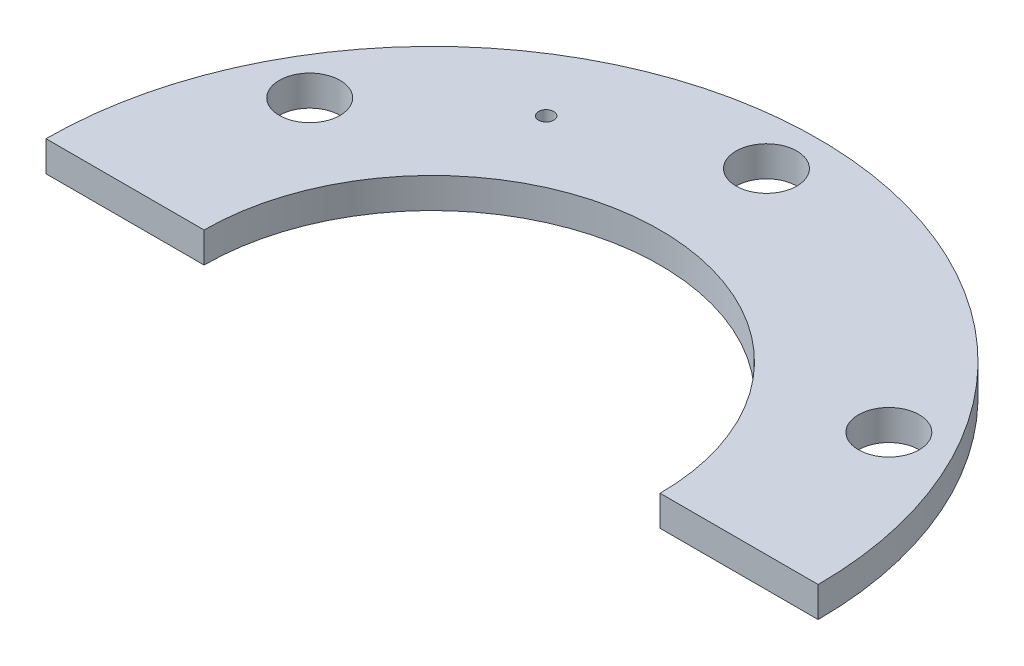
SolidWorks part; units mm, degrees
material "ABS"
ref_plane "Front Plane" through (0, 0, 0) normal (0, 0, 1) x (1, 0, 0)
ref_plane "Top Plane" through (0, 0, 0) normal (0, 1, 0) x (1, 0, 0)
ref_plane "Right Plane" through (0, 0, 0) normal (1, 0, 0) x (0, 0, -1)
sketch "Sketch1" plane through (0, 0, 0) normal (0, 1, 0) x (1, 0, 0)
  circle A0 centre (0, 0) radius 12.7
  dimension "D1" = 25.4
extrude "Boss-Extrude1" add sketch "Sketch1" along normal blind 1
sketch "Sketch19" plane through (0, 1, 0) normal (0, 1, 0) x (1, 0, 0)
  circle A0 centre (0, 11) radius 1
  circle A1 centre (9.5263, 5.5) radius 1
  circle A2 centre (9.5263, -5.5) radius 1
  circle A3 centre (0, -11) radius 1
  circle A4 centre (-9.5263, -5.5) radius 1
  circle A5 centre (-9.5263, 5.5) radius 1
  point P13 (0, 0)
  dimension "D1" = 2
  dimension "D2" = 11
  dimension "D3" = 6
extrude "Cut-Extrude1" cut sketch "Sketch19" against normal through all both and the other way through all
sketch "Sketch20" plane through (0, 1, 0) normal (0, 1, 0) x (1, 0, 0)
  circle A0 centre (0, 0) radius 7.5
  dimension "D1" = 15
extrude "Cut-Extrude2" cut sketch "Sketch20" against normal through all both and the other way through all
sketch "Sketch21" plane through (0, 0, 0) normal (0, 0, 1) x (1, 0, 0)
  line L1 (-36.7533, 32.3113) -> (29.1209, 32.3113)
  line L2 (-36.7533, 32.3113) -> (-36.7533, -19.668)
  line L3 (-36.7533, -19.668) -> (29.1209, -19.668)
  line L4 (29.1209, 32.3113) -> (29.1209, -19.668)
extrude "Cut-Extrude3" cut sketch "Sketch21" along normal through all
sketch "Sketch22" plane through (0, 1, 0) normal (0, 1, 0) x (1, 0, 0)
  line L0 (-9.5263, 5.5) -> (0, 11)
  line L1 (0, 0) -> (-5.125, 8.8768) construction
  circle A0 centre (-5.125, 8.8768) radius 0.25
  dimension "D1" = 0.5
  dimension "D2" = 10.25
extrude "Cut-Extrude4" cut sketch "Sketch22" against normal through all both and the other way through all
